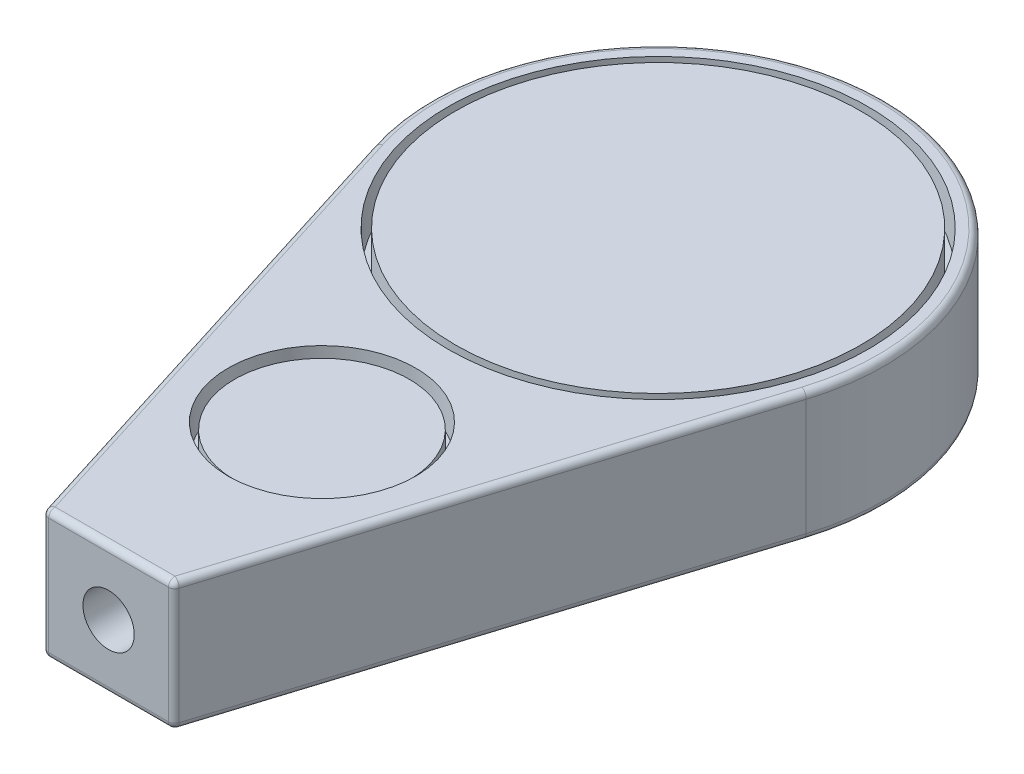
SolidWorks part; units mm, degrees
ref_plane "Front Plane" through (0, 0, 0) normal (0, 0, 1) x (1, 0, 0)
ref_plane "Top Plane" through (0, 0, 0) normal (0, 1, 0) x (1, 0, 0)
ref_plane "Right Plane" through (0, 0, 0) normal (1, 0, 0) x (0, 0, -1)
sketch "Sketch1" plane through (0, 0, 0) normal (0, 1, 0) x (1, 0, 0)
  circle A0 centre (0, 0) radius 35
  dimension "D1" = 70
extrude "Boss-Extrude1" add sketch "Sketch1" along normal blind 20 contours A0
sketch "Sketch2" plane through (0, 20, 0) normal (0, 1, 0) x (1, 0, 0)
  circle A0 centre (0, 0) radius 32.5
  dimension "D1" = 65
extrude "Cut-Extrude1" cut sketch "Sketch2" against normal blind 6.5
sketch "Sketch3" plane through (0, 13.5, 0) normal (0, 1, 0) x (1, 0, 0)
  circle A0 centre (0, 0) radius 31.35
  dimension "D1" = 62.7
extrude "Boss-Extrude2" add sketch "Sketch3" along normal up to surface (6.5 mm away) up to face at (0, 20, 32.5)
sketch "Sketch8" plane through (0, 0, 0) normal (0, 1, 0) x (1, 0, 0)
  line L0 (-33.3932, -10.4832) -> (-10, -85)
  line L1 (-10, -85) -> (10, -85)
  line L2 (10, -85) -> (33.3932, -10.4832)
  circle A0 centre (0, 0) radius 35
  circle A1 centre (0, 0) radius 35 construction
  point P7 (0, -85)
  dimension "D1" = 85
  dimension "D2" = 20
extrude "Boss-Extrude3" add sketch "Sketch8" along normal up to surface (20 mm away) contours A0 L0 L1 L2 up to face at (0, 20, 31.35)
sketch "Sketch14" plane through (0, 20, 0) normal (0, 1, 0) x (1, 0, 0)
  line L0 (-10, -85) -> (10, -85) construction
  circle A0 centre (0, -52) radius 14.5
  point P2 (0, -85)
  dimension "D1" = 29
  dimension "D2" = 33
extrude "Cut-Extrude2" cut sketch "Sketch14" against normal blind 5
sketch "Sketch15" plane through (0, 15, 0) normal (0, 1, 0) x (1, 0, 0)
  circle A0 centre (0, -52) radius 13.5
  circle A1 centre (0, -52) radius 14.5 construction
  dimension "D1" = 27
extrude "Boss-Extrude4" add sketch "Sketch15" along normal blind 4
hole_wizard "Tap Drill for 3/8-16 Tap1" positions "Sketch12" profile "Sketch13" hole size "3/8-16" standard "ANSI Inch"
sketch "Sketch12" plane through (0, 0, 85) normal (0, 0, 1) x (1, 0, 0)
  line L0 (-10, 20) -> (10, 20) construction
  line L4 (10, 20) -> (10, 0) construction
  point P0 (0, 10)
  point P6 (0, 20)
  point P16 (10, 10)
sketch "Sketch13" plane through (0, 10, 85) normal (1, 0, 0) x (0, -1, 0)
  line L0 (0, 0) -> (0, 42.3847)
  line L1 (0, 42.3847) -> (3.9687, 40)
  line L2 (3.9687, 40) -> (3.9687, 0)
  line L5 (3.9687, 0) -> (0, 0)
  line L10 (0, 42.3847) -> (-3.9688, 40) construction
  line L11 (0, -6.35) -> (0, 107.95) construction
  dimension "Hole Dia." = 7.9375
  dimension "Hole Depth" = 40
  dimension "Drill Angle" = 118
fillet "Fillet1" radius 1 10 edges at (21.6966, 20, 47.7416) (21.6966, 0, 47.7416) (0, 0, -35) (0, 20, -35) (10, 10, 85) (0, 20, 85) (0, 0, 85) (-10, 10, 85) (-21.6966, 20, 47.7416) (-21.6966, 0, 47.7416)
